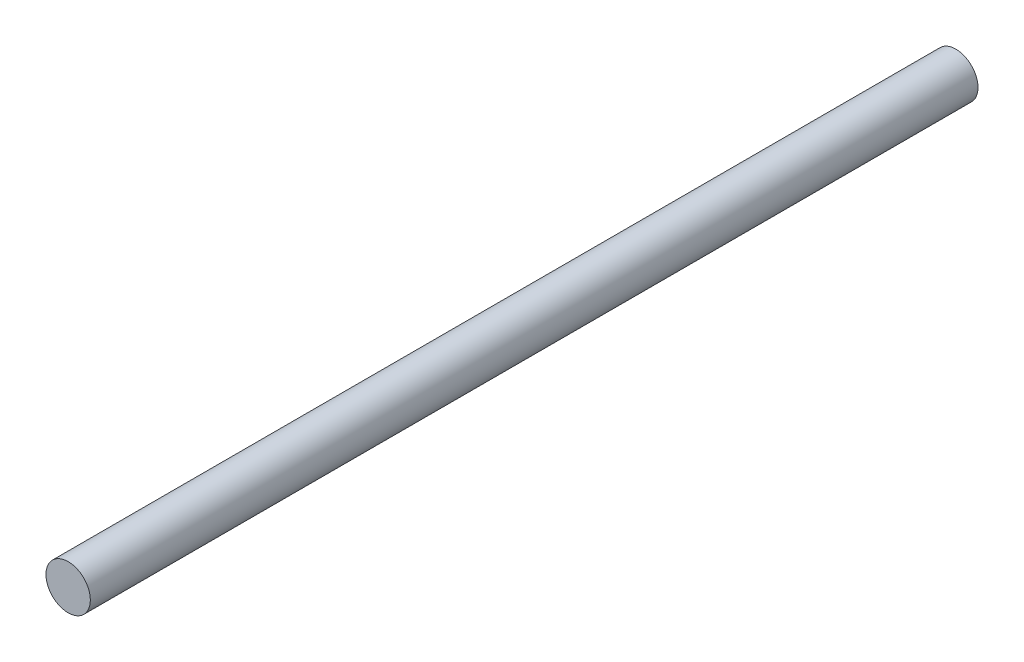
SolidWorks part; units mm, degrees
ref_plane "Ön Düzlem" through (0, 0, 0) normal (0, 0, 1) x (1, 0, 0)
ref_plane "Üst Düzlem" through (0, 0, 0) normal (0, 1, 0) x (1, 0, 0)
ref_plane "Sağ Düzlem" through (0, 0, 0) normal (1, 0, 0) x (0, 0, -1)
sketch "Sketch1" plane through (0, 0, 0) normal (0, 0, 1) x (1, 0, 0)
  circle A0 centre (0, 0) radius 6.25
  dimension "D1" = 12.5
extrude "Boss-Extrude1" add sketch "Sketch1" along normal blind 250
sketch "Sketch2" plane through (0, 0, 250) normal (0, 0, 1) x (1, 0, 0)
  circle A0 centre (0, 0) radius 8
  dimension "D1" = 16
